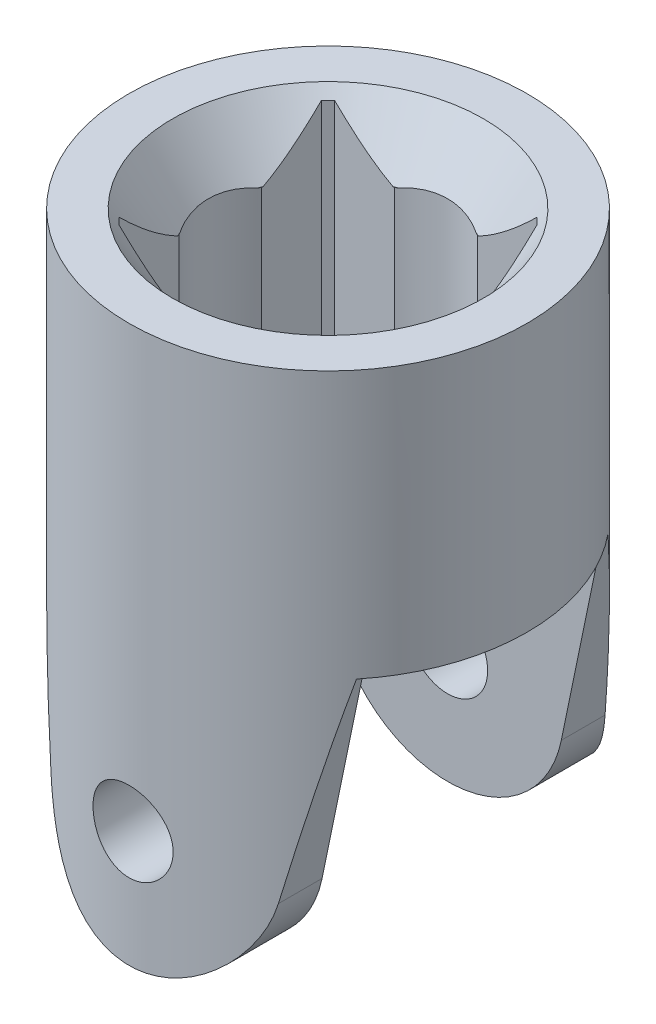
SolidWorks part; units mm, degrees
ref_plane "Front Plane" through (0, 0, 0) normal (0, 0, 1) x (1, 0, 0)
ref_plane "Top Plane" through (0, 0, 0) normal (0, 1, 0) x (1, 0, 0)
ref_plane "Right Plane" through (0, 0, 0) normal (1, 0, 0) x (0, 0, -1)
sketch "Sketch1" plane through (0, 0, 0) normal (0, 1, 0) x (1, 0, 0)
  circle A0 centre (0, 0) radius 12
  dimension "D1" = 24
extrude "Boss-Extrude1" add sketch "Sketch1" along normal blind 33.53
sketch "Sketch2" plane through (0, 33.53, 0) normal (0, 1, 0) x (1, 0, 0)
  line L0 (-6.5, 6.5) -> (-2.5, 6.5)
  line L1 (-6.5, 6.5) -> (6.5, 6.5) construction
  line L2 (-6.5, 6.5) -> (-6.5, -6.5) construction
  line L3 (-6.5, -6.5) -> (6.5, -6.5) construction
  line L4 (6.5, 6.5) -> (6.5, -6.5) construction
  line L5 (-6.5, 6.5) -> (6.5, -6.5) construction
  line L6 (-6.5, -6.5) -> (6.5, 6.5) construction
  line L7 (2.5, 6.5) -> (6.5, 6.5)
  line L8 (6.5, 6.5) -> (6.5, 2.5)
  line L9 (6.5, -2.5) -> (6.5, -6.5)
  line L10 (6.5, -6.5) -> (2.5, -6.5)
  line L11 (-2.5, -6.5) -> (-6.5, -6.5)
  line L12 (-6.5, -6.5) -> (-6.5, -2.5)
  line L13 (-6.5, 2.5) -> (-6.5, 6.5)
  arc A0 (-2.5, 6.5) -> (2.5, 6.5) centre (0, 2.4611) cw
  arc A1 (6.5, 2.5) -> (6.5, -2.5) centre (2.4611, 0) cw
  arc A2 (2.5, -6.5) -> (-2.5, -6.5) centre (0, -2.4611) cw
  arc A3 (-6.5, -2.5) -> (-6.5, 2.5) centre (-2.4611, 0) cw
  point P0 (0, 0)
  point P9 (0, 7.2111)
  point P28 (0, 0)
  dimension "D3" = 4.75
  dimension "D1" = 13
  dimension "D2" = 4
  dimension "D4" = 4
extrude "Cut-Extrude1" cut sketch "Sketch2" against normal blind 19.6
chamfer "Chamfer1" distance 0.4 angle 45 4 edges at (-6.5, 23.73, 6.5) (6.5, 23.73, 6.5) (-6.5, 23.73, -6.5) (6.5, 23.73, -6.5)
sketch "Sketch3" plane through (0, 33.53, 0) normal (0, 1, 0) x (1, 0, 0)
  circle A0 centre (0, 0) radius 9.375
  dimension "D1" = 18.75
extrude "Cut-Extrude2" cut sketch "Sketch3" against normal blind 3.4 draft 35
sketch "Sketch4" plane through (0, 0, 0) normal (0, -1, 0) x (1, 0, 0)
  line L1 (-12, 7.2111) -> (12, 7.2111)
  line L2 (-12, 7.2111) -> (-12, -7.2111)
  line L3 (-12, -7.2111) -> (12, -7.2111)
  line L4 (12, 7.2111) -> (12, -7.2111)
  arc A0 (2.5, 6.5) -> (-2.5, 6.5) centre (0, 2.4611) ccw construction
  arc A1 (-2.5, -6.5) -> (2.5, -6.5) centre (0, -2.4611) ccw construction
  circle A2 centre (0, 0) radius 12 construction
extrude "Cut-Extrude3" cut sketch "Sketch4" against normal blind 17.4
sketch "Sketch5" plane through (0, 0, 0) normal (0, 0, 1) x (1, 0, 0)
  line L0 (12, 17.4) -> (9.3, 17.4)
  line L1 (9.3, 17.4) -> (6.8548, 5.5817)
  line L2 (0, 0) -> (0, 33.53) construction
  line L3 (12, 33.53) -> (-12, 33.53) construction
  line L4 (-12, 17.4) -> (-9.3, 17.4)
  line L5 (-9.3, 17.4) -> (-6.8548, 5.5817)
  line L6 (-6.8548, 5.5817) -> (6.8548, 5.5817) construction
  line L7 (-12, 17.4) -> (-12, -3.1923)
  line L8 (-12, -3.1923) -> (12, -3.1923)
  line L9 (12, -3.1923) -> (12, 17.4)
  arc A0 (-6.8548, 5.5817) -> (6.8548, 5.5817) centre (0, 7) ccw
  circle A1 centre (0, 7) radius 2.415
  dimension "D1" = 7
  dimension "D3" = 4.83
  dimension "D2" = 2.7
extrude "Cut-Extrude4" cut sketch "Sketch5" against normal mid plane 67.4 contours A1 | A0 L5 L4 L7 L8 L9 L0 L1
scale "Scale1" scale about centroid uniform scaling yes scale factor 0.49
